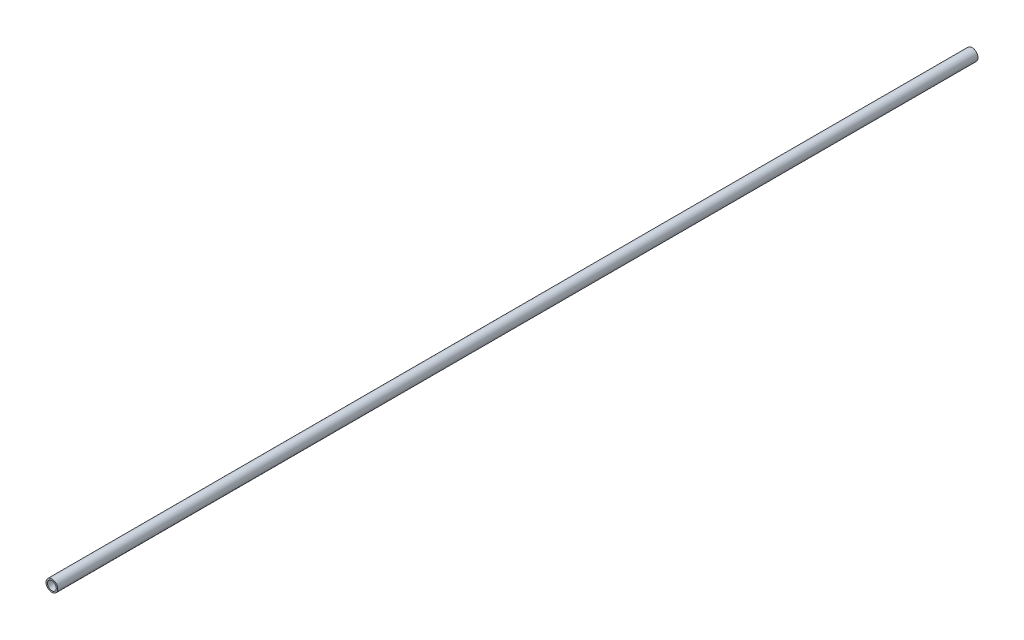
SolidWorks part; units mm, degrees
ref_plane "Front Plane" through (0, 0, 0) normal (0, 0, 1) x (1, 0, 0)
ref_plane "Top Plane" through (0, 0, 0) normal (0, 1, 0) x (1, 0, 0)
ref_plane "Right Plane" through (0, 0, 0) normal (1, 0, 0) x (0, 0, -1)
sketch "Sketch1" plane through (0, 0, 0) normal (0, 0, 1) x (1, 0, 0)
  circle A0 centre (0, 0) radius 40
  dimension "D1" = 80
extrude "Extrude-Thin1" add sketch "Sketch1" along normal blind 6270 thin thin type one direction reverse wall 10
